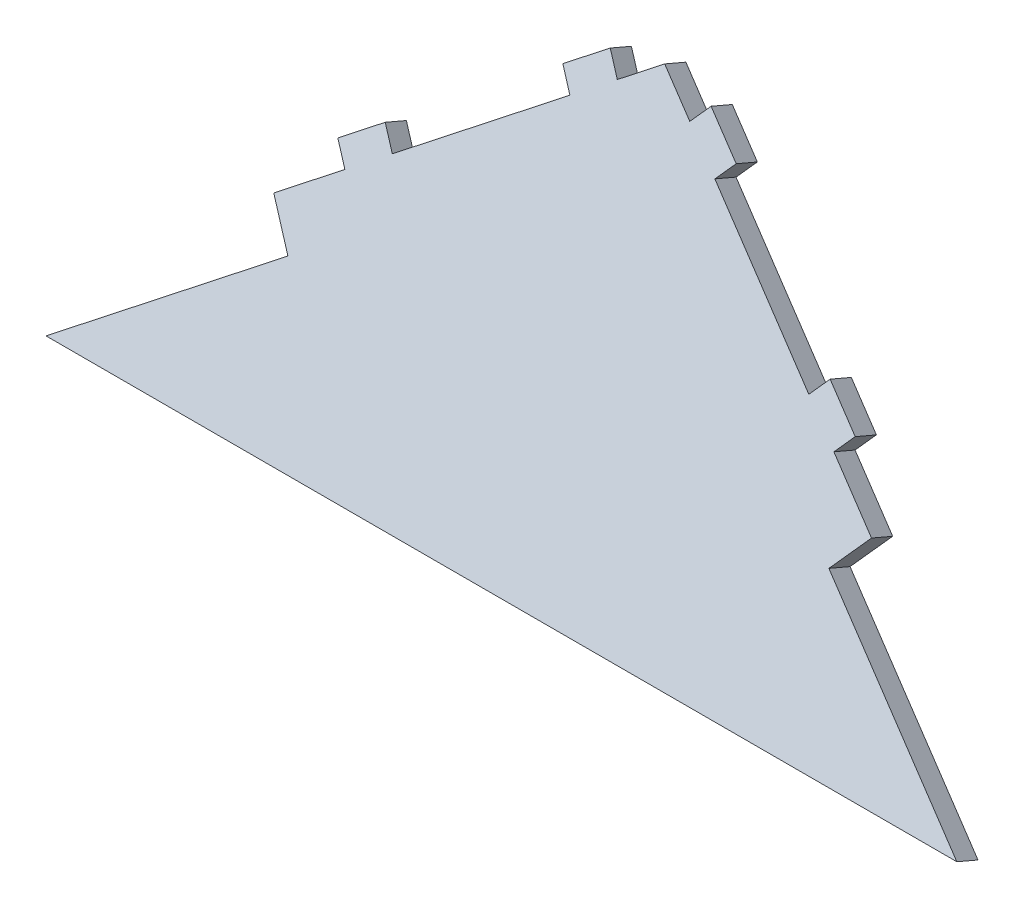
SolidWorks part; units mm, degrees
ref_plane "Plan de face" through (0, 0, 0) normal (0, 0, 1) x (1, 0, 0)
ref_plane "Plan de dessus" through (0, 0, 0) normal (0, 1, 0) x (1, 0, 0)
ref_plane "Plan de droite" through (0, 0, 0) normal (1, 0, 0) x (0, 0, -1)
sketch3d "Esquisse3D1"
  line L0 (0, 0, 0) -> (-64.9259, -46.74, 0) construction
  line L1 (-64.9259, -46.74, 0) -> (64.9259, -46.74, 0) construction
  line L2 (64.9259, -46.74, 0) -> (0, 0, 0) construction
  line L3 (0, 0, 0) -> (0, -46.74, 0) construction
  line L4 (0, 0, 0) -> (0, 0, -20) construction
  line L5 (0, 0, -20) -> (-7.8734, -5.6681, -17.5746)
  line L6 (0, 0, -20) -> (7.8734, -5.6681, -17.5746)
  line L7 (-64.9259, -46.74, 0) -> (-50, -66.74, 0) construction
  line L8 (-50, -66.74, 0) -> (50, -66.74, 0) construction
  line L9 (50, -66.74, 0) -> (64.9259, -46.74, 0) construction
  line L10 (0, -46.74, 0) -> (0, -66.74, 0) construction
  line L11 (0, 0, -20) -> (0, -15.7095, -56.7131) construction
  line L12 (64.9259, -46.74, 0) -> (58.7608, -53.9786, 3.0974)
  line L13 (58.7608, -53.9786, 3.0974) -> (98.9352, -82.9, 15.4729)
  line L14 (98.9352, -82.9, 15.4729) -> (-98.9352, -82.9, 15.4729)
  line L15 (-64.9259, -46.74, 0) -> (-58.7608, -53.9786, 3.0974)
  line L16 (-58.7608, -53.9786, 3.0974) -> (-98.9352, -82.9, 15.4729)
  line L17 (53.1158, -38.2379, -3.638) -> (56.1984, -34.6186, -5.1867)
  line L18 (48.3249, -28.9505, -7.6121) -> (56.1984, -34.6186, -5.1867)
  line L19 (48.3249, -28.9505, -7.6121) -> (45.2424, -32.5698, -6.0634)
  line L20 (53.1158, -38.2379, -3.638) -> (64.9259, -46.74, 0)
  line L21 (15.7468, -11.3361, -15.1493) -> (18.8294, -7.7168, -16.698)
  line L22 (18.8294, -7.7168, -16.698) -> (10.956, -2.0488, -19.1233)
  line L23 (10.956, -2.0488, -19.1233) -> (7.8734, -5.6681, -17.5746)
  line L24 (15.7468, -11.3361, -15.1493) -> (45.2424, -32.5698, -6.0634)
  line L25 (-7.8734, -5.6681, -17.5746) -> (-10.956, -2.0488, -19.1233)
  line L26 (-10.956, -2.0488, -19.1233) -> (-18.8294, -7.7168, -16.698)
  line L27 (-18.8294, -7.7168, -16.698) -> (-15.7468, -11.3361, -15.1493)
  line L28 (-53.1158, -38.2379, -3.638) -> (-56.1984, -34.6186, -5.1867)
  line L29 (-48.3249, -28.9505, -7.6121) -> (-56.1984, -34.6186, -5.1867)
  line L30 (-48.3249, -28.9505, -7.6121) -> (-45.2424, -32.5698, -6.0634)
  line L31 (-53.1158, -38.2379, -3.638) -> (-64.9259, -46.74, 0)
  line L32 (-15.7468, -11.3361, -15.1493) -> (-45.2424, -32.5698, -6.0634)
  dimension "D1" = 108.5
  dimension "D2" = 20
  dimension "D3" = 80
  dimension "D4" = 100
  dimension "D5" = 20
  dimension "D6" = 130
  dimension "D7" = 10
  dimension "D8" = 10
  dimension "D9" = 5
  dimension "D10" = 15
  dimension "D11" = 10
  dimension "D12" = 10
extrude "Boss.-Extru.2" add sketch "Esquisse3D1" along direction (0, -0.3934, -0.9194) on the side of the normal blind 5
